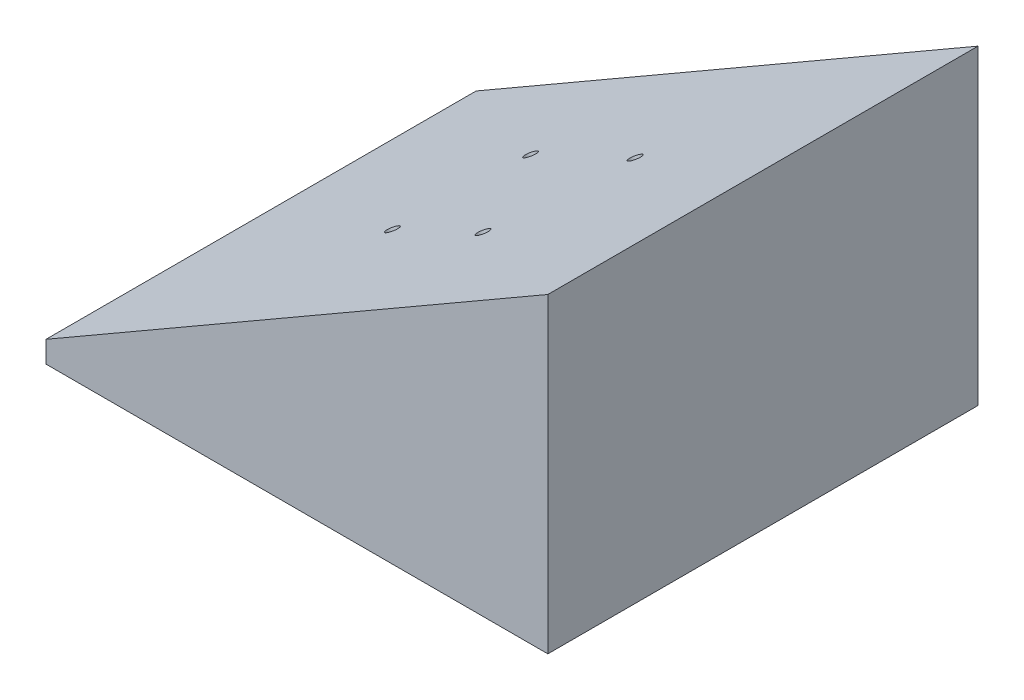
SolidWorks part; units mm, degrees
ref_plane "前视基准面" through (0, 0, 0) normal (0, 0, 1) x (1, 0, 0)
ref_plane "上视基准面" through (0, 0, 0) normal (0, 1, 0) x (1, 0, 0)
ref_plane "右视基准面" through (0, 0, 0) normal (1, 0, 0) x (0, 0, -1)
other "Configuration Table"
sketch "草图1" plane through (0, 0, 0) normal (0, 0, 1) x (1, 0, 0)
  line L0 (0, 0) -> (70, 0)
  line L1 (70, 0) -> (70, 43.4145)
  line L2 (70, 43.4145) -> (0, 3)
  line L3 (0, 3) -> (0, 0)
extrude "凸台-拉伸1" add sketch "草图1" along normal blind 60
sketch "草图2" plane through (-1.299, 2.25, 0) normal (-0.5, 0.866, 0) x (0.866, 0.5, 0)
  circle A0 centre (32.7935, -19.503) radius 0.85
  circle A1 centre (53.8015, -23.123) radius 0.85
  circle A2 centre (49.3745, -40.502) radius 0.85
  circle A3 centre (31.1735, -37.391) radius 0.85
extrude "切除-拉伸1" cut sketch "草图2" against normal mid plane 60
